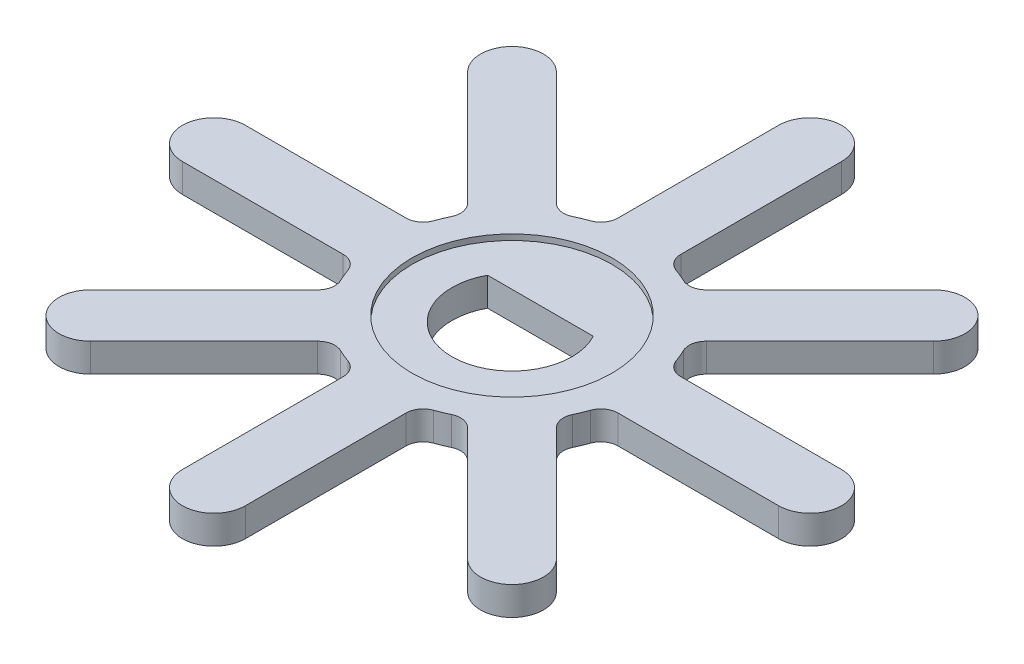
SolidWorks part; units mm, degrees
material "2014 Alloy"
ref_plane "Front Plane" through (0, 0, 0) normal (0, 0, 1) x (1, 0, 0)
ref_plane "Top Plane" through (0, 0, 0) normal (0, 1, 0) x (1, 0, 0)
ref_plane "Right Plane" through (0, 0, 0) normal (1, 0, 0) x (0, 0, -1)
sketch "Sketch1" plane through (0, 0, 0) normal (0, 1, 0) x (1, 0, 0)
  line L0 (-6.985, 66.2517) -> (-6.985, 27.7081)
  line L1 (6.985, 66.2517) -> (6.985, 27.7081)
  line L2 (51.7861, 41.9079) -> (24.5317, 14.6535)
  line L3 (41.9079, 51.7861) -> (14.6535, 24.5317)
  line L4 (66.2517, -6.985) -> (27.7081, -6.985)
  line L5 (66.2517, 6.985) -> (27.7081, 6.985)
  line L6 (41.9079, -51.7861) -> (14.6535, -24.5317)
  line L7 (51.7861, -41.9079) -> (24.5317, -14.6535)
  line L8 (-6.985, -66.2517) -> (-6.985, -27.7081)
  line L9 (6.985, -66.2517) -> (6.985, -27.7081)
  line L10 (-51.7861, -41.9079) -> (-24.5317, -14.6535)
  line L11 (-41.9079, -51.7861) -> (-14.6535, -24.5317)
  line L12 (-66.2517, 6.985) -> (-27.7081, 6.985)
  line L13 (-66.2517, -6.985) -> (-27.7081, -6.985)
  line L14 (-41.9079, 51.7861) -> (-14.6535, 24.5317)
  line L15 (-51.7861, 41.9079) -> (-24.5317, 14.6535)
  circle A1 centre (0, 0) radius 73.2367 construction
  arc A2 (-24.5317, 14.6535) -> (-27.7081, 6.985) centre (0, 0) ccw
  arc A3 (-6.985, 66.2517) -> (6.985, 66.2517) centre (0, 66.2517) cw
  arc A4 (41.9079, 51.7861) -> (51.7861, 41.9079) centre (46.847, 46.847) cw
  arc A5 (66.2517, 6.985) -> (66.2517, -6.985) centre (66.2517, 0) cw
  arc A6 (51.7861, -41.9079) -> (41.9079, -51.7861) centre (46.847, -46.847) cw
  arc A7 (6.985, -66.2517) -> (-6.985, -66.2517) centre (0, -66.2517) cw
  arc A8 (-41.9079, -51.7861) -> (-51.7861, -41.9079) centre (-46.847, -46.847) cw
  arc A9 (-66.2517, -6.985) -> (-66.2517, 6.985) centre (-66.2517, 0) cw
  arc A10 (-51.7861, 41.9079) -> (-41.9079, 51.7861) centre (-46.847, 46.847) cw
  arc A11 (-6.985, 27.7081) -> (-14.6535, 24.5317) centre (0, 0) ccw
  arc A12 (14.6535, 24.5317) -> (6.985, 27.7081) centre (0, 0) ccw
  arc A13 (27.7081, 6.985) -> (24.5317, 14.6535) centre (0, 0) ccw
  arc A14 (24.5317, -14.6535) -> (27.7081, -6.985) centre (0, 0) ccw
  arc A15 (6.985, -27.7081) -> (14.6535, -24.5317) centre (0, 0) ccw
  arc A16 (-14.6535, -24.5317) -> (-6.985, -27.7081) centre (0, 0) ccw
  arc A17 (-27.7081, -6.985) -> (-24.5317, -14.6535) centre (0, 0) ccw
  point P7 (0, 0)
  point P8 (0, 73.2367)
  point P11 (0, 0)
  point P12 (0, 0)
  point P48 (0, 0)
  point P49 (0, 0)
  point P50 (0, 0)
  point P51 (6.985, -68.622)
  point P52 (0, 0)
  dimension "D1" = 6.985
  dimension "D2" = 146.4733
  dimension "D3" = 57.15
  dimension "D4" = 8
extrude "Boss-Extrude1" add sketch "Sketch1" along normal blind 6.35
fillet "Fillet1" radius 3.81 16 edges at (-14.6535, 3.175, -24.5317) (-6.985, 3.175, -27.7081) (6.985, 3.175, -27.7081) (14.6535, 3.175, -24.5317) (24.5317, 3.175, -14.6535) (27.7081, 3.175, -6.985) (27.7081, 3.175, 6.985) (24.5317, 3.175, 14.6535) (14.6535, 3.175, 24.5317) (6.985, 3.175, 27.7081) (-6.985, 3.175, 27.7081) (-14.6535, 3.175, 24.5317) (-24.5317, 3.175, 14.6535) (-27.7081, 3.175, 6.985) (-27.7081, 3.175, -6.985) (-24.5317, 3.175, -14.6535)
sketch "Sketch2" plane through (0, 6.35, 0) normal (0, 1, 0) x (1, 0, 0)
  circle A0 centre (0, 0) radius 22.225
  dimension "D1" = 44.45
extrude "Cut-Extrude1" cut sketch "Sketch2" against normal blind 1.27
sketch "Sketch3" plane through (0, 5.08, 0) normal (0, 1, 0) x (1, 0, 0)
  line L0 (-11.7475, 6.3102) -> (11.7475, 6.3102)
  arc A0 (-11.7475, 6.3102) -> (11.7475, 6.3102) centre (0, 0) ccw
  dimension "D1" = 26.67
  dimension "D2" = 23.495
extrude "Cut-Extrude2" cut sketch "Sketch3" against normal through all
sketch "Sketch4" plane through (0, 0, 0) normal (0, -1, 0) x (1, 0, 0)
  line L0 (-13.0175, -11.1578) -> (13.0175, -11.1578)
  line L1 (11.7475, -6.3102) -> (-11.7475, -6.3102)
  arc A0 (13.0175, -11.1578) -> (-13.0175, -11.1578) centre (0, 0) ccw
  arc A1 (11.7475, -6.3102) -> (-11.7475, -6.3102) centre (0, 0) ccw
  dimension "D1" = 34.29
  dimension "D2" = 26.035
extrude "Boss-Extrude3" add sketch "Sketch4" along normal blind 1.27
